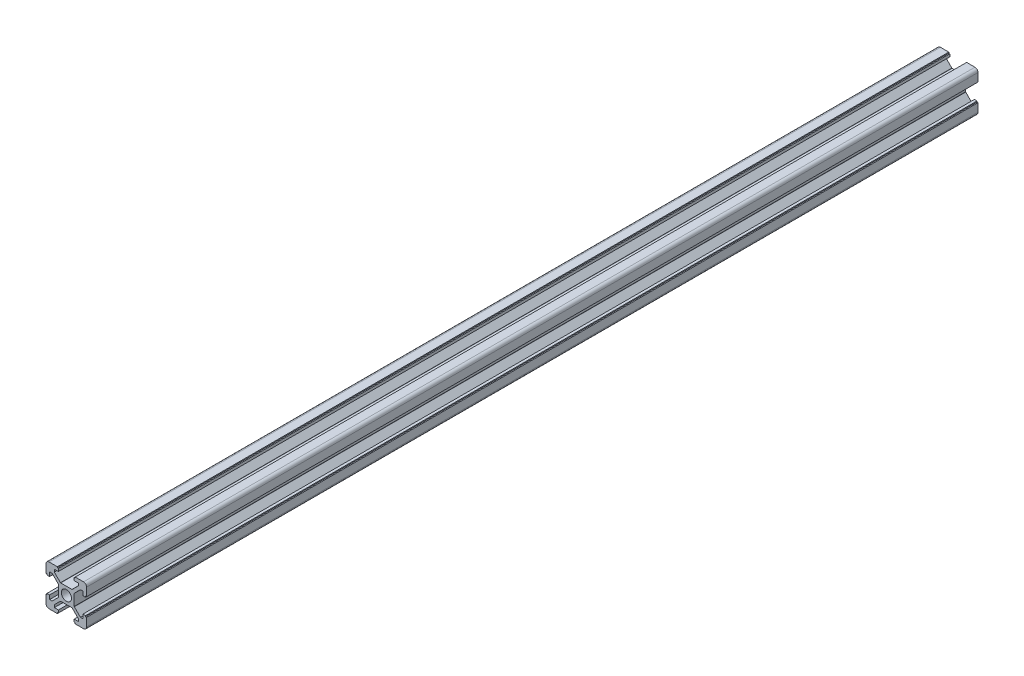
SolidWorks part; units mm, degrees
ref_plane "前视基准面" through (0, 0, 0) normal (0, 0, 1) x (1, 0, 0)
ref_plane "上视基准面" through (0, 0, 0) normal (0, 1, 0) x (1, 0, 0)
ref_plane "右视基准面" through (0, 0, 0) normal (1, 0, 0) x (0, 0, -1)
other "Configuration Table"
sketch "草图1" plane through (0, 0, 0) normal (0, 0, 1) x (1, 0, 0)
  line L0 (-10, 0) -> (10, 0) construction
  line L1 (-10, 10) -> (-4.4, 10)
  line L2 (-10, 10) -> (-10, 4.4)
  line L3 (-10, -10) -> (-4.4, -10)
  line L4 (10, 10) -> (10, 4.4)
  line L5 (-10, 10) -> (10, -10) construction
  line L6 (-10, -10) -> (10, 10) construction
  line L7 (-2.8396, 3.9001) -> (2.8395, 3.9001)
  line L8 (-3.9, 2.8393) -> (-3.9, -2.8395)
  line L9 (-2.8393, -3.9) -> (2.8395, -3.9)
  line L10 (3.9001, 2.8396) -> (3.9001, -2.8395)
  line L11 (-3.9, 3.9) -> (3.9, -3.9) construction
  line L12 (-3.9, -3.9) -> (3.9, 3.9) construction
  line L13 (0.0284, 9.9716) -> (0.0284, -10) construction
  line L14 (-6.9607, 5.9) -> (-3.9, 2.8393)
  line L15 (-5.9, 6.9607) -> (-2.8396, 3.9001)
  line L16 (-6.9607, 5.9) -> (-8.2, 5.9)
  line L17 (-8.2, 5.9) -> (-8.2, 3.9)
  line L18 (-8.2, 3.9) -> (-9.5, 3.9)
  line L19 (-9.5, 3.9) -> (-9.5, 4.4)
  line L20 (-9.5, 4.4) -> (-10, 4.4)
  line L21 (-5.9, 6.9607) -> (-5.9, 8.2)
  line L22 (-5.9, 8.2) -> (-3.9, 8.2)
  line L23 (-3.9, 8.2) -> (-3.9, 9.5)
  line L24 (-3.9, 9.5) -> (-4.4, 9.5)
  line L25 (-4.4, 9.5) -> (-4.4, 10)
  line L26 (6.9607, 5.9) -> (3.9001, 2.8396)
  line L27 (5.9, 6.9607) -> (2.8393, 3.9)
  line L28 (5.9, 6.9607) -> (5.9, 8.2)
  line L29 (5.9, 8.2) -> (3.9, 8.2)
  line L30 (3.9, 8.2) -> (3.9, 9.5)
  line L31 (3.9, 9.5) -> (4.4, 9.5)
  line L32 (4.4, 9.5) -> (4.4, 10)
  line L33 (6.9607, 5.9) -> (8.2, 5.9)
  line L34 (8.2, 5.9) -> (8.2, 3.9)
  line L35 (8.2, 3.9) -> (9.5, 3.9)
  line L36 (9.5, 3.9) -> (9.5, 4.4)
  line L37 (9.5, 4.4) -> (10, 4.4)
  line L38 (5.9, -6.9607) -> (2.8395, -3.9)
  line L39 (6.9607, -5.9) -> (3.9, -2.8393)
  line L40 (6.9607, -5.9) -> (8.2, -5.9)
  line L41 (8.2, -5.9) -> (8.2, -3.9)
  line L42 (8.2, -3.9) -> (9.5, -3.9)
  line L43 (9.5, -3.9) -> (9.5, -4.4)
  line L44 (9.5, -4.4) -> (10, -4.4)
  line L45 (5.9, -6.9607) -> (5.9, -8.2)
  line L46 (5.9, -8.2) -> (3.9, -8.2)
  line L47 (3.9, -8.2) -> (3.9, -9.5)
  line L48 (3.9, -9.5) -> (4.4, -9.5)
  line L49 (4.4, -9.5) -> (4.4, -10)
  line L50 (-6.9607, -5.9) -> (-3.9, -2.8395)
  line L51 (-5.9, -6.9607) -> (-2.8393, -3.9)
  line L52 (-5.9, -6.9607) -> (-5.9, -8.2)
  line L53 (-5.9, -8.2) -> (-3.9, -8.2)
  line L54 (-3.9, -8.2) -> (-3.9, -9.5)
  line L55 (-3.9, -9.5) -> (-4.4, -9.5)
  line L56 (-4.4, -9.5) -> (-4.4, -10)
  line L57 (-6.9607, -5.9) -> (-8.2, -5.9)
  line L58 (-8.2, -5.9) -> (-8.2, -3.9)
  line L59 (-8.2, -3.9) -> (-9.5, -3.9)
  line L60 (-9.5, -3.9) -> (-9.5, -4.4)
  line L61 (-9.5, -4.4) -> (-10, -4.4)
  line L62 (4.4, -10) -> (10, -10)
  line L63 (-10, -4.4) -> (-10, -10)
  line L64 (10, -10) -> (10, -4.4)
  line L65 (4.4, 10) -> (10, 10)
  circle A0 centre (0.0284, -0.0142) radius 2.5
  point P0 (0, 0)
  point P6 (0, 0)
  point P18 (0, 0)
  point P32 (0, 0)
  point P76 (0, 0)
  dimension "D6" = 5
  dimension "D1" = 20
  dimension "D3" = 7.8
  dimension "D4" = 7.8
  dimension "D5" = 0.75
  dimension "D7" = 0.5
  dimension "D8" = 0.5
  dimension "D9" = 1.8
  dimension "D10" = 6.1
  dimension "D12" = 2
  dimension "D11" = 4
extrude "凸台-拉伸1" add sketch "草图1" along normal blind 439
fillet "圆角1" radius 1.5 4 edges at (10, -10, 219.5) (-10, -10, 219.5) (-10, 10, 219.5) (10, 10, 219.5)
fillet "圆角2" radius 0.2 8 edges at (3.9001, -2.8395, 219.5) (3.9001, 2.8396, 219.5) (-2.8393, -3.9, 219.5) (2.8395, -3.9, 219.5) (-2.8396, 3.9001, 219.5) (2.8395, 3.9001, 219.5) (-3.9, 2.8393, 219.5) (-3.9, -2.8395, 219.5)
